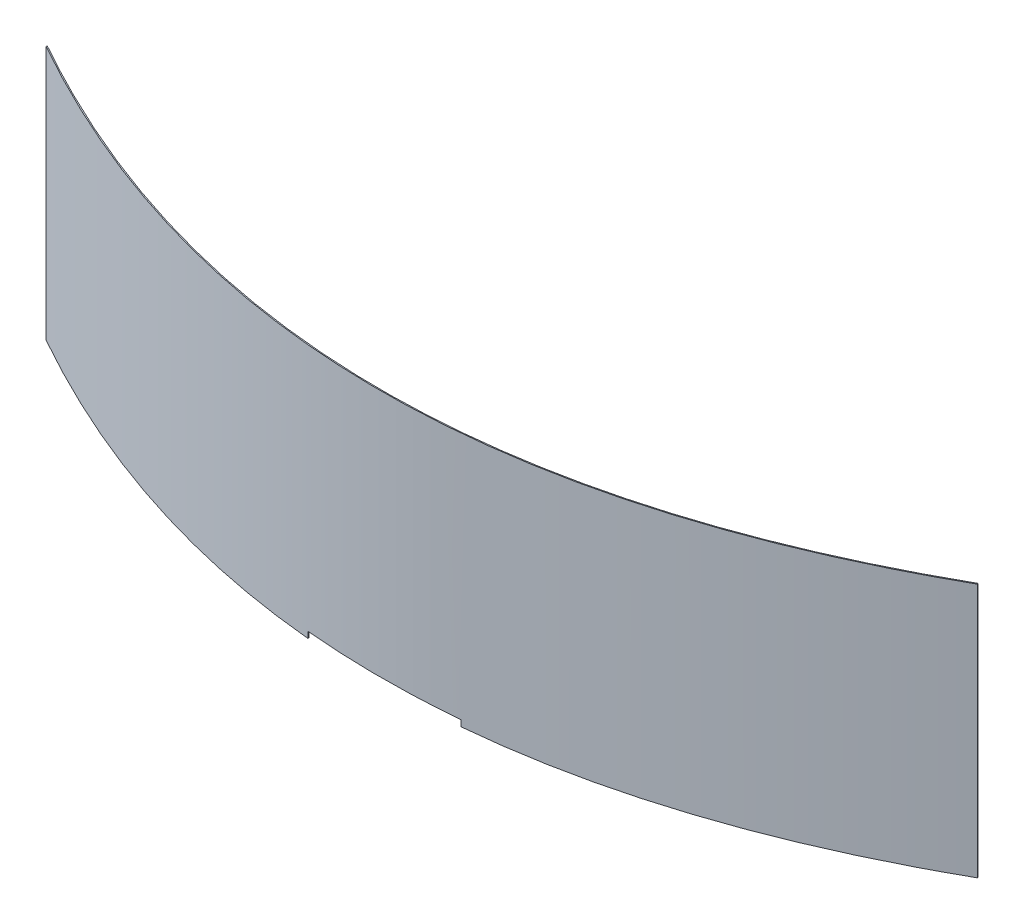
SolidWorks part; units mm, degrees
ref_plane "Front Plane" through (0, 0, 0) normal (0, 0, 1) x (1, 0, 0)
ref_plane "Top Plane" through (0, 0, 0) normal (0, 1, 0) x (1, 0, 0)
ref_plane "Right Plane" through (0, 0, 0) normal (1, 0, 0) x (0, 0, -1)
sketch "Sketch1" plane through (0, 0, 0) normal (0, 1, 0) x (1, 0, 0)
  line L0 (0, -200) -> (0, 0) construction
  line L1 (-225, -136.7187) -> (225, -136.7187) construction
  line L4 (-225, -136.7187) -> (-225.2451, -137.1545)
  line L5 (225.2451, -137.1545) -> (225, -136.7187)
  parabola Q0 (-225, -136.7187) -> (225, -136.7187) focus (0, 0) apex (0, -200)
  spline S0 degree 1 poles (-225.2451, -137.1545) (225.2451, -137.1545) knots 0 0 1 1 construction
  spline S1 degree 3 poles (-225.2451, -137.1545) (-222.9082, -138.4691) (-218.2041, -141.0739) (-208.8273, -146.1009) (-197.0951, -152.0818) (-183.0206, -158.7616) (-164.2523, -167.0094) (-140.7912, -176.0823) (-112.6357, -184.9909) (-84.4784, -191.9202) (-46.9336, -198.52) (0, -201.82) (46.9336, -198.52) (84.4784, -191.9202) (112.6357, -184.9909) (140.7912, -176.0823) (164.2523, -167.0094) (183.0206, -158.7616) (197.0951, -152.0818) (208.8273, -146.1009) (218.2041, -141.0739) (222.9082, -138.4691) (225.2451, -137.1545) knots 0.496023 0.496023 0.496023 0.496023 0.496147 0.496271 0.49652 0.496768 0.497017 0.497514 0.498011 0.498508 0.499006 0.5 0.500994 0.501492 0.501989 0.502486 0.502983 0.503232 0.50348 0.503729 0.503853 0.503977 0.503977 0.503977 0.503977
  dimension "D2" = 200
  dimension "D3" = 0.5
extrude "Boss-Extrude1" add sketch "Sketch1" along normal blind 123
sketch "Sketch2" plane through (0, 0, 0) normal (0, 0, 1) x (1, 0, 0)
  line L0 (-225, 0) -> (225, 0) construction
  line L1 (37, 3) -> (-37, 3)
  line L2 (37, 3) -> (37, 0)
  line L3 (37, 0) -> (-37, 0)
  line L4 (-37, 3) -> (-37, 0)
  point P4 (0, 0)
  dimension "D1" = 74
  dimension "D2" = 3
extrude "Cut-Extrude1" cut sketch "Sketch2" along normal up to surface (198.7909 mm away)
